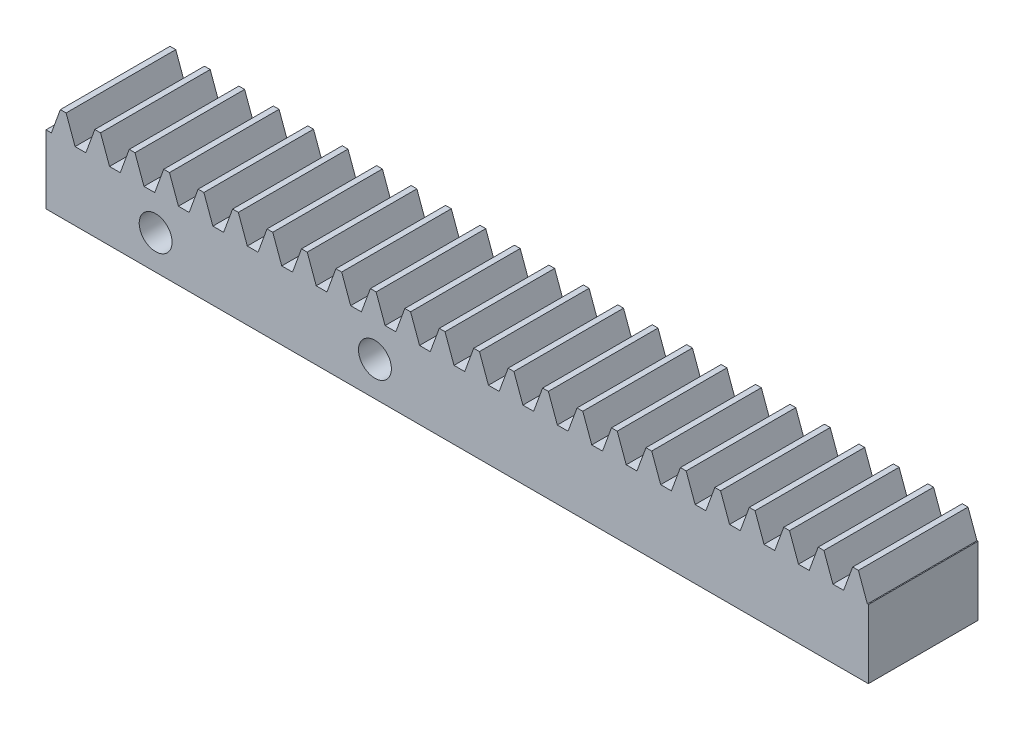
SolidWorks part; units mm, degrees
extrude "Blank" add sketch "BlankSke" against normal blind 10
sketch "BlankSke" plane through (0, 0, 0) normal (0, 0, 1) x (1, 0, 0)
  line L1 (0, 0) -> (75, 0)
  line L2 (0, 0) -> (0, 8.5)
  line L3 (0, 8.5) -> (75, 8.5)
  line L4 (75, 0) -> (75, 8.5)
  dimension "Length" = 75
  dimension "Blank_height" = 8.5
ref_plane "Plane1" through (0, 0, 0) normal (0, 0, 1) x (1, 0, 0)
ref_plane "Plane2" through (0, 0, 0) normal (0, 1, 0) x (1, 0, 0)
ref_plane "Plane3" through (0, 0, 0) normal (1, 0, 0) x (0, 0, -1)
other "Configuration Table"
sketch "HoldingSke" plane through (0, 0, 0) normal (0, 1, 0) x (1, 0, 0)
  line L0 (0, 0) -> (0.1392, 0.9903)
  line L1 (-15, 0) -> (100, 0) construction
  line L2 (0, 0) -> (-2.1039, 2.3779)
  line L3 (0, 0) -> (-11.863, 4.5341)
  line L4 (0, 0) -> (7.8269, 3.6497)
  line L5 (0, 0) -> (-23.7986, -8.8762)
  line L6 (0, 0) -> (-10.5278, -7.1032)
  line L9 (-71.009, 38.7566) -> (-0.532, 64.4081)
  line L10 (-76.2, 3.3779) -> (-68.7, 3.3779)
  line L11 (0, 0) -> (-10, 0)
  line L12 (-76.2, 101.6) -> (-76.147, 101.6)
  line L13 (24.9733, 27.94) -> (52.9518, 28.4284)
  line L14 (24.9733, 27.94) -> (24.9743, 27.94)
  line L15 (24.9733, 27.94) -> (100.4006, 29.5858)
  circle A0 centre (0, 0) radius 19.05
  circle A1 centre (0, 0) radius 3.75
  circle A2 centre (0, 0) radius 12.7
  dimension "MPH" = 7.5
  dimension "Diameter" = 38.1
  dimension "Num_teeth" = 25
  dimension "Pitch" = 1
  dimension "Show_teeth" = 998
  dimension "Thickness" = 12.7
  dimension "Ap" = 20
  dimension "Pitch_height" = 7.5
  dimension "Width" = 10
  dimension "Backlash" = 0.053
  dimension "Addendum_fac" = 1
  dimension "Dedendum_fac" = 1.25
  dimension "Clearance_fac" = 0.25
  dimension "Dedendum_add" = 0.001
  dimension "Length" = 75
  dimension "Module" = 1
sketch "TooCutSkeIll" plane through (0, 0, 0) normal (0, 0, 1) x (1, 0, 0)
  line L0 (-1.2988, 8.4737) -> (-0.5495, 6.4152)
  line L1 (-0.3137, 6.25) -> (0.3137, 6.25)
  line L2 (0.5495, 6.4152) -> (1.2988, 8.4737)
  line L3 (75, 8.5) -> (0, 8.5) construction
  line L4 (0, 0) -> (0, 64.897) construction
  line L5 (-13.208, 7.5) -> (12.954, 7.5) construction
  line L6 (0, 0) -> (75, 0) construction
  line L7 (0.9444, 7.5) -> (0.9444, 48.7463) construction
  line L8 (-0.9444, 7.5) -> (-0.9444, 48.7463) construction
  line L9 (1.3364, 8.5) -> (1.3364, 8.5254)
  line L10 (-1.3364, 8.5) -> (-1.3364, 8.5254)
  line L11 (-1.3364, 8.5254) -> (1.3364, 8.5254)
  arc A0 (0.3137, 6.25) -> (0.5495, 6.4152) centre (0.3137, 6.501) ccw
  arc A1 (-0.5495, 6.4152) -> (-0.3137, 6.25) centre (-0.3137, 6.501) ccw
  arc A2 (1.3364, 8.5) -> (1.2988, 8.4737) centre (1.3364, 8.46) ccw
  arc A3 (-1.2988, 8.4737) -> (-1.3364, 8.5) centre (-1.3364, 8.46) ccw
  dimension "Pitch_height" = 7.5
  dimension "Addendum_plus" = 1.0254
  dimension "Pressure_angle" = 20
  dimension "Gap_width" = 1.8888
  dimension "Dedendum" = 1.25
extrude "ToothCutIll" [suppressed] cut sketch "TooCutSkeIll" against normal through all
sketch "TooCutSkeSim" plane through (0, 0, 0) normal (0, 0, 1) x (1, 0, 0)
  line L0 (0.4894, 6.25) -> (-0.4894, 6.25)
  line L1 (1.3176, 8.5254) -> (0.4894, 6.25)
  line L2 (0, 17.4625) -> (0, 53.467) construction
  line L3 (1.3176, 8.5254) -> (-1.3176, 8.5254)
  line L6 (-1.3176, 8.5254) -> (-0.4894, 6.25)
  line L9 (-0.9444, 7.5) -> (0.9444, 7.5) construction
  line L10 (0, 0) -> (75, 0) construction
  line L11 (0.9444, 7.5) -> (0.9444, 53.467) construction
  line L12 (-0.9444, 7.5) -> (-0.9444, 53.467) construction
  dimension "Pitch_height" = 7.5
  dimension "Addendum_plus" = 1.0254
  dimension "Pressure_angle" = 20
  dimension "Gap_width" = 1.8888
  dimension "Dedendum" = 1.25
extrude "ToothCutSim" cut sketch "TooCutSkeSim" against normal through all
pattern_linear "TeethCuts" count 25 spacing 3.1416 along (1, 0, 0) of "ToothCutIll", "ToothCutSim"
sketch "Sketch1" plane through (0, 0, 0) normal (0, 0, 1) x (1, 0, 0)
  line L0 (0, 3.125) -> (75, 3.125) construction
  line L1 (0, 6.25) -> (0, 0) construction
  line L2 (75, 0) -> (75, 6.25) construction
  circle A0 centre (10, 3.125) radius 1.5
  circle A1 centre (30, 3.125) radius 1.5
  point P10 (0, 0)
  point P11 (0, 0)
  point P12 (0, 0)
  point P13 (0, 0)
  point P14 (30, 2.6563)
  dimension "D1" = 3
  dimension "D2" = 3
  dimension "D3" = 20
  dimension "D4" = 10
extrude "Cut-Extrude1" cut sketch "Sketch1" against normal up to surface (10 mm away) up to face at (37.6911, 7.205, -10)
equation "' \"Module@HoldingSke\" = 6.35"
equation "' \"Num_teeth@HoldingSke\" = 12"
equation "' \"Ap@HoldingSke\" =  20"
equation "' \"Ap@HoldingSke\" = 20"
equation "' \"Width@HoldingSke\" = 0.25 * 25.4"
equation "' \"Show_teeth@HoldingSke\" = 500"
equation "' \"Backlash@HoldingSke\" = 0.009 * 25.4"
equation "' \"Addendum_fac@HoldingSke\" = 1.0"
equation "' \"Dedendum_fac@HoldingSke\" = 1.25"
equation "' \"Dedendum_add@HoldingSke\" = 0.00005 * 25.4"
equation "' \"Clearance_fac@HoldingSke\" = 0.25"
equation "' \"Pitch_height@HoldingSke\" = 1 * 25.4"
equation "' \"Length@HoldingSke\" = 4.71 * 25.4"
equation "\"Pitch@HoldingSke\" = 1 / \"Module@HoldingSke\""
equation "\"MPH@HoldingSke\" = \"Dedendum_fac@HoldingSke\" / \"Pitch@HoldingSke\" + 2 * \"Dedendum_add@HoldingSke\" + 0.002 * 25.4"
equation "\"MPH@HoldingSke\" = ((sgn( \"MPH@HoldingSke\" - \"Pitch_height@HoldingSke\")+1)*( \"MPH@HoldingSke\" - \"Pitch_height@HoldingSke\"))/2 + \"Pitch_height@HoldingSke\""
equation "\"Blank_height@BlankSke\" = \"Pitch_height@HoldingSke\" + \"Addendum_fac@HoldingSke\"  / \"Pitch@HoldingSke\" "
equation "\"Length@BlankSke\"= \"Length@HoldingSke\""
equation "\"Face_width@Blank\" = \"Width@HoldingSke\""
equation "\"Pressure_angle@TooCutSkeIll\" = \"Ap@HoldingSke\""
equation "\"Addendum_plus@TooCutSkeIll\" =  \"Addendum_fac@HoldingSke\"  / \"Pitch@HoldingSke\" + 0.001 *25.4"
equation "\"Dedendum@TooCutSkeIll\" = \"Dedendum_fac@HoldingSke\"  / \"Pitch@HoldingSke\""
equation "\"Pitch_height@TooCutSkeIll\" =  \"MPH@HoldingSke\""
equation "\"Gap_width@TooCutSkeIll\" = 3.14159265 / 2 / \"Pitch@HoldingSke\" + 6 * \"Backlash@HoldingSke\""
equation "\"Pressure_angle@TooCutSkeSim\" = \"Ap@HoldingSke\""
equation "\"Addendum_plus@TooCutSkeSim\" =  \"Addendum_fac@HoldingSke\"  / \"Pitch@HoldingSke\" + 0.001 * 25.4"
equation "\"Dedendum@TooCutSkeSim\" = \"Dedendum_fac@HoldingSke\"  / \"Pitch@HoldingSke\""
equation "\"Pitch_height@TooCutSkeSim\" =  \"MPH@HoldingSke\""
equation "\"Gap_width@TooCutSkeSim\" = 3.14159265 / 2 / \"Pitch@HoldingSke\" + 6 * \"Backlash@HoldingSke\""
equation "\"Root_fillet@TooCutSkeIll\" = \"Clearance_fac@HoldingSke\" / \"Pitch@HoldingSke\" + \"Dedendum_add@HoldingSke\""
equation "\"Break_rad@TooCutSkeIll\" = 0.02 / \"Pitch@HoldingSke\" * 2"
equation "\"Linear_pitch@TeethCuts\" = 3.14159265 / \"Pitch@HoldingSke\""
equation "\"Num_teeth@HoldingSke\" = int( ( \"Length@HoldingSke\" + 0 ) / (3.14159265 / \"Pitch@HoldingSke\")) + 0.9999  + 1"
equation " \"Num_teeth@TeethCuts\" = int( \"Show_teeth@HoldingSke\" ) + 1"
equation " \"Num_teeth@TeethCuts\" = ((sgn( \"Num_teeth@TeethCuts\" - \"Num_teeth@HoldingSke\" )-1)*( \"Num_teeth@TeethCuts\" - \"Num_teeth@HoldingSke\" ))/-2+ \"Num_teeth@HoldingSke\""
equation "\"Num_teeth@TeethCuts\"= ( ( sgn ( \"Num_teeth@TeethCuts\" - 2.0 ) + 1 ) * ( \"Num_teeth@TeethCuts\" - 2.0 ) ) / 2 + 6"
